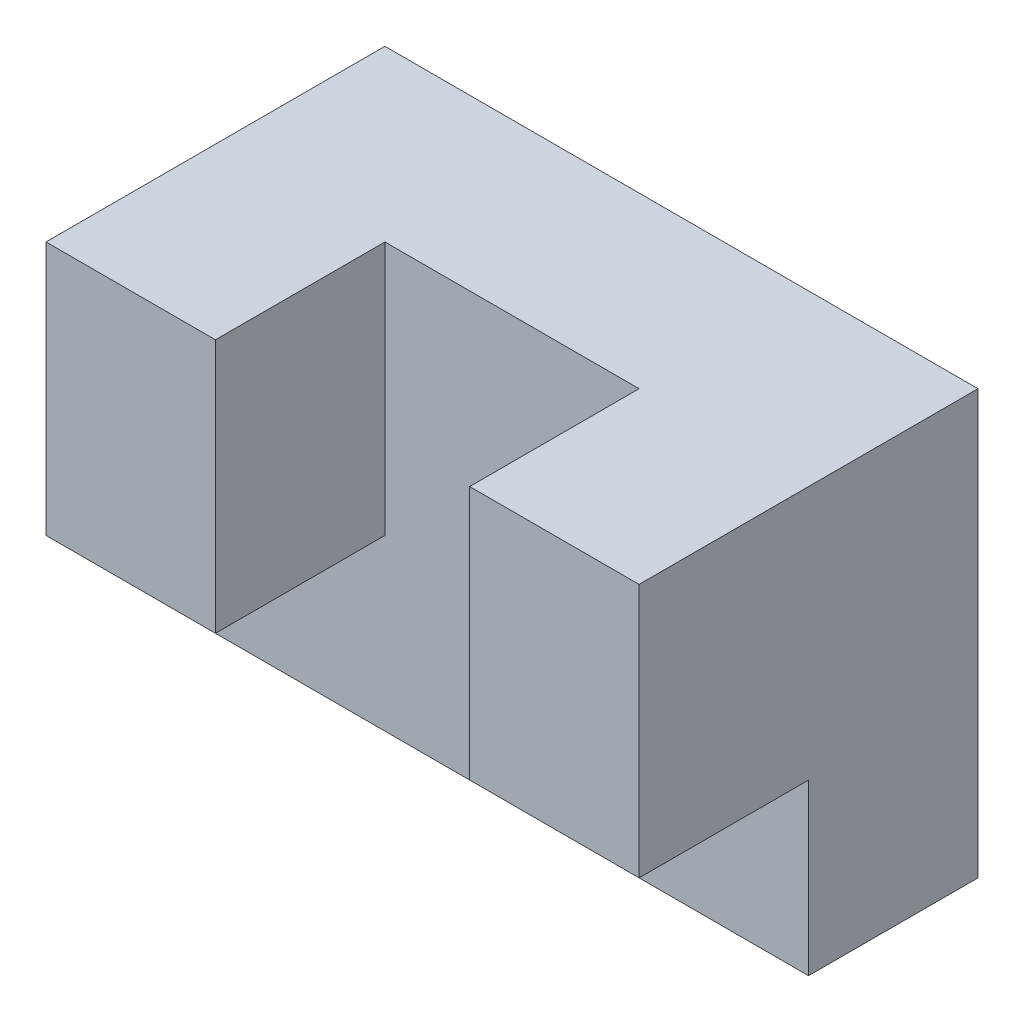
SolidWorks part; units mm, degrees
ref_plane "Alzado" through (0, 0, 0) normal (0, 0, 1) x (1, 0, 0)
ref_plane "Planta" through (0, 0, 0) normal (0, 1, 0) x (1, 0, 0)
ref_plane "Vista lateral" through (0, 0, 0) normal (1, 0, 0) x (0, 0, -1)
sketch "Croquis2" plane through (0, 0, 0) normal (0, 0, 1) x (1, 0, 0)
  line L1 (-35, -25) -> (35, -25)
  line L2 (-35, -25) -> (-35, 25)
  line L3 (-35, 25) -> (35, 25)
  line L4 (35, -25) -> (35, 25)
  line L5 (-35, -25) -> (35, 25) construction
  line L6 (-35, 25) -> (35, -25) construction
  point P0 (0, 0)
  dimension "D1" = 50
  dimension "D2" = 70
extrude "Saliente-Extruir1" add sketch "Croquis2" along normal blind 20
sketch "Croquis3" plane through (0, 0, 20) normal (0, 0, 1) x (1, 0, 0)
  line L1 (-35, 25) -> (-15, 25)
  line L2 (-35, 25) -> (-35, -5)
  line L3 (-35, -5) -> (-15, -5)
  line L4 (-15, 25) -> (-15, -5)
  line L5 (35, 25) -> (15, 25)
  line L6 (35, 25) -> (35, -5)
  line L7 (35, -5) -> (15, -5)
  line L8 (15, 25) -> (15, -5)
  dimension "D1" = 30
  dimension "D2" = 20
  dimension "D3" = 30
  dimension "D4" = 20
extrude "Saliente-Extruir2" add sketch "Croquis3" along normal blind 20
sketch "Croquis4" plane through (0, -25, 0) normal (0, -1, 0) x (-1, 0, 0)
  line L0 (35, -8.9161) -> (-35, -8.9161) construction
  line L1 (35, -20) -> (35, 0) construction
  line L2 (-35, -20) -> (-35, 0) construction
  text T0 "SOLIDWORKS 2026"
